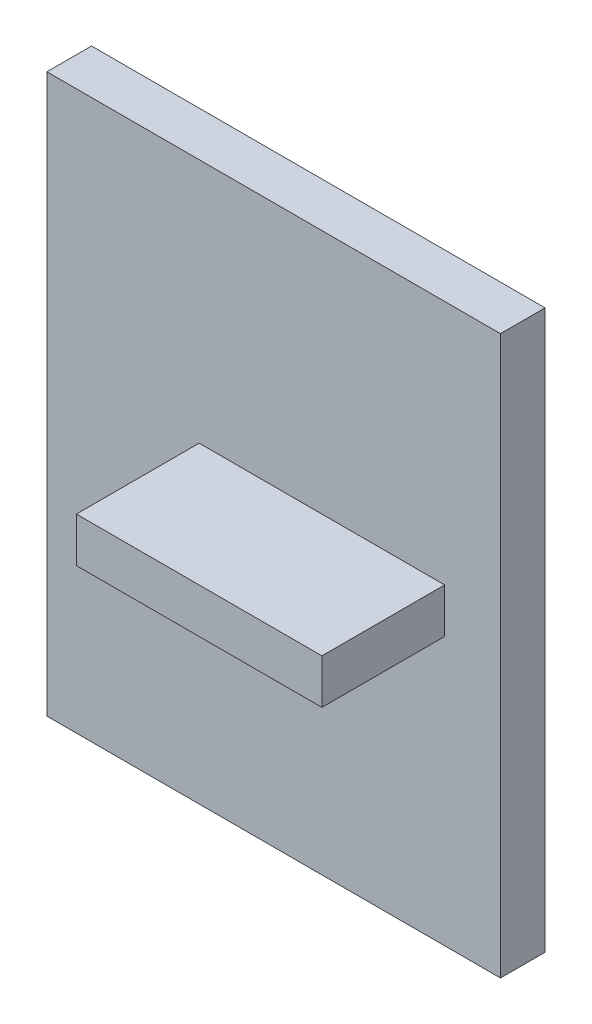
SolidWorks part; units mm, degrees
ref_plane "Front Plane" through (0, 0, 0) normal (0, 0, 1) x (1, 0, 0)
ref_plane "Top Plane" through (0, 0, 0) normal (0, 1, 0) x (1, 0, 0)
ref_plane "Right Plane" through (0, 0, 0) normal (1, 0, 0) x (0, 0, -1)
sketch "Sketch1" plane through (0, 0, 0) normal (0, 0, 1) x (1, 0, 0)
  line L1 (-101.6, -125) -> (101.6, -125)
  line L2 (-101.6, -125) -> (-101.6, 125)
  line L3 (-101.6, 125) -> (101.6, 125)
  line L4 (101.6, -125) -> (101.6, 125)
  line L5 (-101.6, -125) -> (101.6, 125) construction
  line L6 (-101.6, 125) -> (101.6, -125) construction
  point P0 (0, 0)
  dimension "D1" = 203.2
  dimension "D2" = 250
extrude "Boss-Extrude1" add sketch "Sketch1" along normal blind 20
sketch "Sketch2" plane through (0, 0, 0) normal (0, 0, -1) x (-1, 0, 0)
  line L1 (33.4, 15) -> (-76.6, 15)
  line L2 (33.4, 15) -> (33.4, -5)
  line L3 (33.4, -5) -> (-76.6, -5)
  line L4 (-76.6, 15) -> (-76.6, -5)
  line L5 (101.6, -125) -> (-101.6, -125) construction
  line L6 (-101.6, -125) -> (-101.6, 125) construction
  dimension "D1" = 20
  dimension "D2" = 140
  dimension "D3" = 110
  dimension "D4" = 25
extrude "Boss-Extrude2" add sketch "Sketch2" against normal blind 55 from offset 20 separate body
